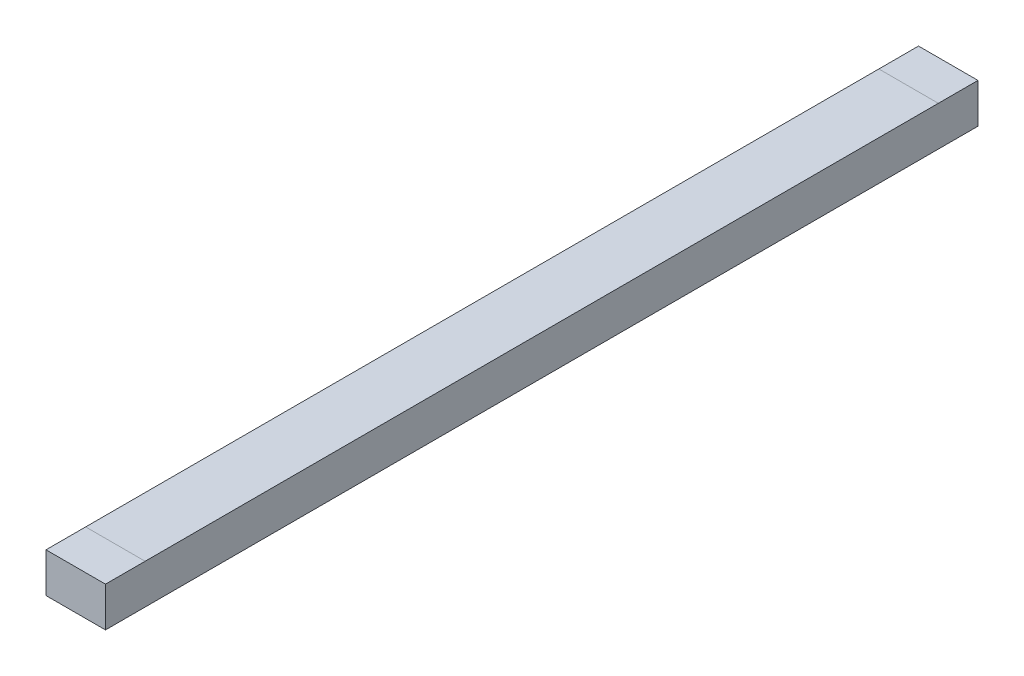
SolidWorks part; units mm, degrees
ref_plane "Płaszczyzna przednia" through (0, 0, 0) normal (0, 0, 1) x (1, 0, 0)
ref_plane "Płaszczyzna górna" through (0, 0, 0) normal (0, 1, 0) x (1, 0, 0)
ref_plane "Płaszczyzna prawa" through (0, 0, 0) normal (1, 0, 0) x (0, 0, -1)
sketch "Szkic1" plane through (0, 0, 0) normal (0, 0, 1) x (1, 0, 0)
  line L1 (0, 0) -> (150, 0)
  line L2 (0, 0) -> (0, 100)
  line L3 (0, 100) -> (150, 100)
  line L4 (150, 0) -> (150, 100)
  dimension "D1" = 100
  dimension "D2" = 150
extrude "Dodanie-wyciągnięcie1" add sketch "Szkic1" along normal blind 2200
sketch "Szkic2" plane through (0, 100, 0) normal (0, 1, 0) x (1, 0, 0)
  line L0 (0, -100) -> (150, -100)
  line L1 (0, -2200) -> (0, 0) construction
  line L2 (150, -2200) -> (150, 0) construction
  line L3 (0, -2100) -> (150, -2100)
  line L4 (150, 0) -> (0, 0) construction
  line L5 (150, -2200) -> (0, -2200) construction
  dimension "D1" = 100
  dimension "D2" = 100
split line "Linia podziałowa1"
